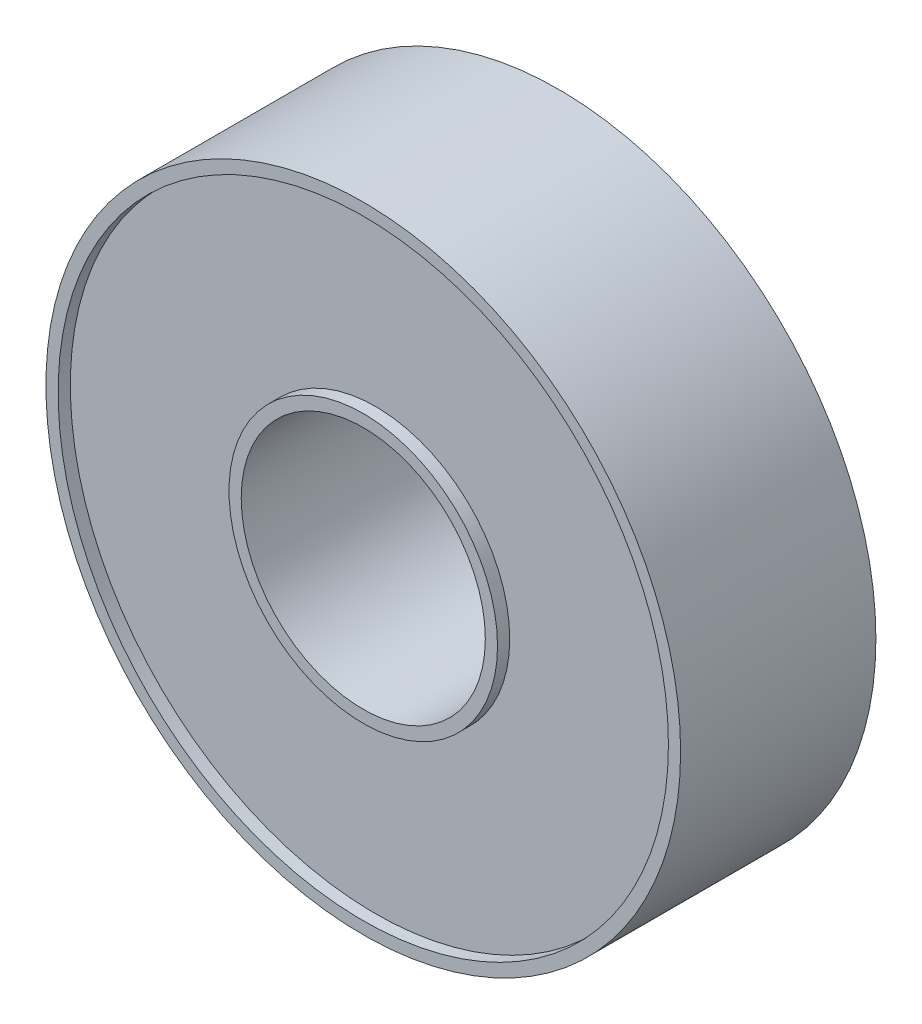
SolidWorks part; units mm, degrees
ref_plane "Front Plane" through (0, 0, 0) normal (0, 0, 1) x (1, 0, 0)
ref_plane "Top Plane" through (0, 0, 0) normal (0, 1, 0) x (1, 0, 0)
ref_plane "Right Plane" through (0, 0, 0) normal (1, 0, 0) x (0, 0, -1)
sketch "Sketch1" plane through (0, 0, 0) normal (0, 0, 1) x (1, 0, 0)
  circle A0 centre (0, 0) radius 13
  circle A1 centre (0, 0) radius 5
  dimension "D1" = 26
  dimension "D2" = 10
extrude "Boss-Extrude1" add sketch "Sketch1" along normal blind 8
sketch "Sketch2" plane through (0, 0, 8) normal (0, 0, 1) x (1, 0, 0)
  circle A2 centre (0, 0) radius 5.5
  circle A3 centre (0, 0) radius 5.5
  circle A5 centre (0, 0) radius 12.5
  circle A6 centre (0, 0) radius 12.5
  dimension "D1" = 0.5
  dimension "D2" = 0.5
extrude "Cut-Extrude1" cut sketch "Sketch2" against normal blind 0.5
ref_plane "Plane1" through (0, 0, 4) normal (0, 0, -1) x (-1, 0, 0)
mirror "Mirror1" about plane through (0, 0, 4) normal (0, 0, -1) of "Cut-Extrude1"
